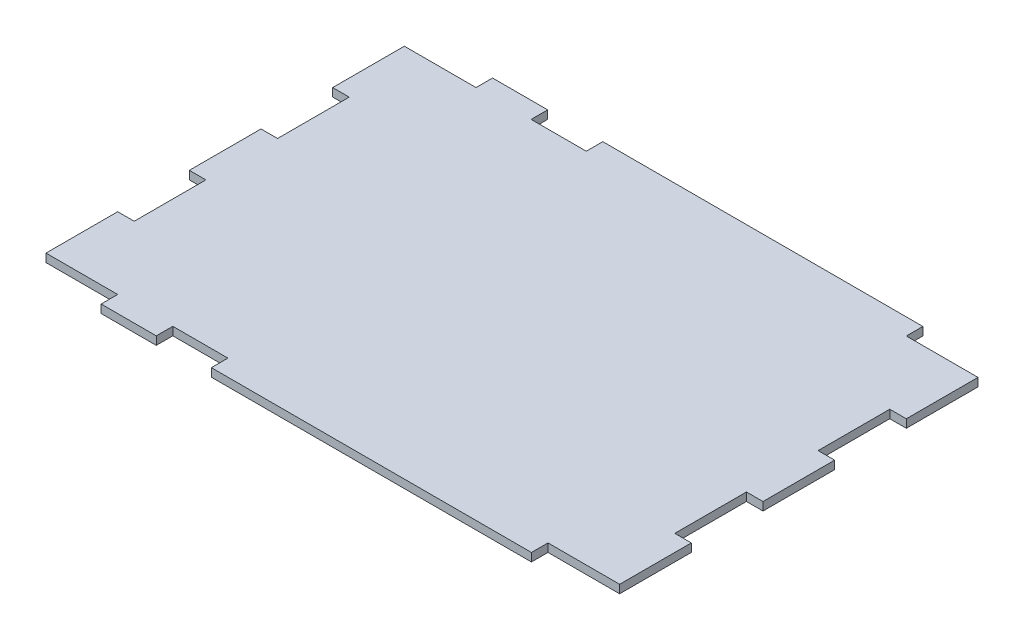
SolidWorks part; units mm, degrees
ref_plane "Front Plane" through (0, 0, 0) normal (0, 0, 1) x (1, 0, 0)
ref_plane "Top Plane" through (0, 0, 0) normal (0, 1, 0) x (1, 0, 0)
ref_plane "Right Plane" through (0, 0, 0) normal (1, 0, 0) x (0, 0, -1)
sketch "Sketch2" plane through (0, 0, 0) normal (0, 1, 0) x (1, 0, 0)
  line L0 (-122.9114, -52) -> (-128.9114, -52)
  line L1 (-122.9114, 78) -> (-102.9114, 78)
  line L3 (-122.9114, -52) -> (-102.9114, -52)
  line L4 (73.1886, 52) -> (73.1886, 26)
  line L5 (-128.9114, -52) -> (-128.9114, -26)
  line L6 (-128.9114, -26) -> (-122.9114, -26)
  line L7 (-122.9114, 0) -> (-128.9114, 0)
  line L8 (-128.9114, 0) -> (-128.9114, 26)
  line L9 (-128.9114, 26) -> (-122.9114, 26)
  line L10 (-122.9114, 52) -> (-122.9114, 26)
  line L11 (-122.9114, 52) -> (-128.9114, 52)
  line L12 (-128.9114, 52) -> (-128.9114, 78)
  line L13 (-128.9114, 78) -> (-122.9114, 78)
  line L14 (-122.9114, 0) -> (-122.9114, -26)
  line L15 (-122.9114, 78) -> (-122.9114, -52) construction
  line L16 (53.1886, 78) -> (79.1886, 78)
  line L18 (79.1886, 52) -> (79.1886, 78)
  line L19 (73.1886, 52) -> (79.1886, 52)
  line L20 (79.1886, 26) -> (73.1886, 26)
  line L21 (79.1886, 0) -> (79.1886, 26)
  line L22 (73.1886, 0) -> (79.1886, 0)
  line L23 (79.1886, -26) -> (73.1886, -26)
  line L24 (79.1886, -52) -> (79.1886, -26)
  line L25 (73.1886, -52) -> (79.1886, -52)
  line L26 (73.1886, 0) -> (73.1886, -26)
  line L27 (-102.9114, 78) -> (-102.9114, 84)
  line L28 (-102.9114, 84) -> (-82.9114, 84)
  line L29 (-82.9114, 84) -> (-82.9114, 78)
  line L30 (-82.9114, 78) -> (-62.9114, 78)
  line L31 (-128.9114, 13) -> (-122.9114, 13) construction
  line L32 (-82.9114, -58) -> (-82.9114, -52)
  line L33 (-102.9114, -58) -> (-82.9114, -58)
  line L34 (-102.9114, -52) -> (-102.9114, -58)
  line L35 (-82.9114, -52) -> (-62.9114, -52)
  line L36 (-62.9114, 78) -> (-62.9114, 84)
  line L37 (-62.9114, 84) -> (53.1886, 84)
  line L38 (53.1886, 84) -> (53.1886, 78)
  line L39 (-128.9114, 13) -> (79.1886, 13) construction
  line L40 (53.1886, -58) -> (53.1886, -52)
  line L41 (-62.9114, -58) -> (53.1886, -58)
  line L42 (-62.9114, -52) -> (-62.9114, -58)
  line L43 (53.1886, -52) -> (73.1886, -52)
  line L44 (-62.9114, 84) -> (-46.5781, 84) construction
  line L45 (-46.5781, 84) -> (-28.1281, 84) construction
  line L46 (-28.1281, 84) -> (39.4586, 84) construction
  line L47 (39.4586, 84) -> (21.0086, 84) construction
  line L48 (-46.5781, 84) -> (-46.5781, -58) construction
  line L49 (-28.1281, 84) -> (-28.1281, -58) construction
  line L50 (21.0086, 84) -> (21.0086, -58) construction
  line L51 (39.4586, 84) -> (39.4586, -58) construction
  dimension "D1" = 196.1
  dimension "D2" = 6
  dimension "D3" = 26
  dimension "D4" = 26
  dimension "D5" = 26
  dimension "D6" = 26
  dimension "D7" = 20
  dimension "D8" = 6
  dimension "D9" = 6
  dimension "D10" = 6
  dimension "D11" = 6
  dimension "D12" = 6
  dimension "D13" = 26
  dimension "D14" = 26
  dimension "D15" = 6
  dimension "D16" = 6
  dimension "D17" = 6
  dimension "D18" = 6
  dimension "D19" = 20
  dimension "D20" = 6
  dimension "D21" = 6
  dimension "D22" = 26
  dimension "D23" = 26
  dimension "D24" = 26
  dimension "D25" = 26
  dimension "D26" = 16.3333
  dimension "D27" = 18.45
  dimension "D28" = 13.73
  dimension "D29" = 18.45
  dimension "D30" = 116.1
extrude "Boss-Extrude1" add sketch "Sketch2" along normal blind 3
sketch "Sketch4" plane through (0, 3, 0) normal (0, 1, 0) x (1, 0, 0)
  line L0 (-48.3469, 71.7805) -> (-48.3469, 56.7805)
  line L1 (-45.8469, 81.7805) -> (-45.8469, 66.7805)
  line L2 (-43.3469, 71.7805) -> (-43.3469, 56.7805)
  line L3 (-40.8469, 81.7805) -> (-40.8469, 66.7805)
  line L4 (-38.3469, 71.7805) -> (-38.3469, 56.7805)
  line L5 (-35.8469, 81.7805) -> (-35.8469, 66.7805)
  line L6 (-33.3469, 71.7805) -> (-33.3469, 56.7805)
  line L7 (-30.8469, 81.7805) -> (-30.8469, 66.7805)
  line L8 (-28.3469, 71.7805) -> (-28.3469, 56.7805)
  line L9 (-25.8469, 81.7805) -> (-25.8469, 66.7805)
  line L10 (-23.3469, 71.7805) -> (-23.3469, 56.7805)
  line L12 (-48.3469, 51.7805) -> (-48.3469, 36.7805)
  line L13 (-45.8469, 61.7805) -> (-45.8469, 46.7805)
  line L14 (-43.3469, 51.7805) -> (-43.3469, 36.7805)
  line L15 (-40.8469, 61.7805) -> (-40.8469, 46.7805)
  line L16 (-38.3469, 51.7805) -> (-38.3469, 36.7805)
  line L17 (-35.8469, 61.7805) -> (-35.8469, 46.7805)
  line L18 (-33.3469, 51.7805) -> (-33.3469, 36.7805)
  line L19 (-30.8469, 61.7805) -> (-30.8469, 46.7805)
  line L20 (-28.3469, 51.7805) -> (-28.3469, 36.7805)
  line L21 (-25.8469, 61.7805) -> (-25.8469, 46.7805)
  line L22 (-23.3469, 51.7805) -> (-23.3469, 36.7805)
  line L24 (-48.3469, 31.7805) -> (-48.3469, 16.7805)
  line L25 (-45.8469, 41.7805) -> (-45.8469, 26.7805)
  line L26 (-43.3469, 31.7805) -> (-43.3469, 16.7805)
  line L27 (-40.8469, 41.7805) -> (-40.8469, 26.7805)
  line L28 (-38.3469, 31.7805) -> (-38.3469, 16.7805)
  line L29 (-35.8469, 41.7805) -> (-35.8469, 26.7805)
  line L30 (-33.3469, 31.7805) -> (-33.3469, 16.7805)
  line L31 (-30.8469, 41.7805) -> (-30.8469, 26.7805)
  line L32 (-28.3469, 31.7805) -> (-28.3469, 16.7805)
  line L33 (-25.8469, 41.7805) -> (-25.8469, 26.7805)
  line L34 (-23.3469, 31.7805) -> (-23.3469, 16.7805)
  line L36 (-48.3469, 11.7805) -> (-48.3469, -3.2195)
  line L37 (-45.8469, 21.7805) -> (-45.8469, 6.7805)
  line L38 (-43.3469, 11.7805) -> (-43.3469, -3.2195)
  line L39 (-40.8469, 21.7805) -> (-40.8469, 6.7805)
  line L40 (-38.3469, 11.7805) -> (-38.3469, -3.2195)
  line L41 (-35.8469, 21.7805) -> (-35.8469, 6.7805)
  line L42 (-33.3469, 11.7805) -> (-33.3469, -3.2195)
  line L43 (-30.8469, 21.7805) -> (-30.8469, 6.7805)
  line L44 (-28.3469, 11.7805) -> (-28.3469, -3.2195)
  line L45 (-25.8469, 21.7805) -> (-25.8469, 6.7805)
  line L46 (-23.3469, 11.7805) -> (-23.3469, -3.2195)
  line L48 (-48.3469, -8.2195) -> (-48.3469, -23.2195)
  line L49 (-45.8469, 1.7805) -> (-45.8469, -13.2195)
  line L50 (-43.3469, -8.2195) -> (-43.3469, -23.2195)
  line L51 (-40.8469, 1.7805) -> (-40.8469, -13.2195)
  line L52 (-38.3469, -8.2195) -> (-38.3469, -23.2195)
  line L53 (-35.8469, 1.7805) -> (-35.8469, -13.2195)
  line L54 (-33.3469, -8.2195) -> (-33.3469, -23.2195)
  line L55 (-30.8469, 1.7805) -> (-30.8469, -13.2195)
  line L56 (-28.3469, -8.2195) -> (-28.3469, -23.2195)
  line L57 (-25.8469, 1.7805) -> (-25.8469, -13.2195)
  line L58 (-23.3469, -8.2195) -> (-23.3469, -23.2195)
  line L60 (-48.3469, -28.2195) -> (-48.3469, -43.2195)
  line L61 (-45.8469, -18.2195) -> (-45.8469, -33.2195)
  line L62 (-43.3469, -28.2195) -> (-43.3469, -43.2195)
  line L63 (-40.8469, -18.2195) -> (-40.8469, -33.2195)
  line L64 (-38.3469, -28.2195) -> (-38.3469, -43.2195)
  line L65 (-35.8469, -18.2195) -> (-35.8469, -33.2195)
  line L66 (-33.3469, -28.2195) -> (-33.3469, -43.2195)
  line L67 (-30.8469, -18.2195) -> (-30.8469, -33.2195)
  line L68 (-28.3469, -28.2195) -> (-28.3469, -43.2195)
  line L69 (-25.8469, -18.2195) -> (-25.8469, -33.2195)
  line L70 (-23.3469, -28.2195) -> (-23.3469, -43.2195)
  line L72 (-48.1958, -48.6466) -> (-48.1958, -58)
  line L73 (-45.8469, -38.2195) -> (-45.8469, -53.2195)
  line L74 (-43.1958, -48.6466) -> (-43.1958, -58)
  line L75 (-40.8469, -38.2195) -> (-40.8469, -53.2195)
  line L76 (-38.3469, -48.6466) -> (-38.3469, -58)
  line L77 (-35.8469, -38.2195) -> (-35.8469, -53.2195)
  line L78 (-33.3739, -48.6466) -> (-33.3739, -58)
  line L79 (-30.8469, -38.2195) -> (-30.8469, -53.2195)
  line L80 (-28.1905, -48.6466) -> (-28.1905, -58)
  line L81 (-25.8469, -38.2195) -> (-25.8469, -53.2195)
  line L82 (-23.3469, -48.6466) -> (-23.3469, -58)
  line L84 (-48.3469, 84) -> (-48.3469, 75.3572)
  line L85 (-43.3469, 84) -> (-43.3469, 75.3572)
  line L86 (-38.3403, 84) -> (-38.3469, 75.3572)
  line L87 (-33.3738, 84) -> (-33.3469, 75.3572)
  line L88 (-28.3738, 84) -> (-28.3469, 75.3572)
  line L89 (-23.3738, 84) -> (-23.3469, 75.3572)
  line L90 (53.1886, 84) -> (-62.9114, 84) construction
  line L91 (-62.9114, -58) -> (53.1886, -58) construction
  line L92 (15.5348, 71.2734) -> (15.5348, 56.2734)
  line L93 (18.0348, 81.2734) -> (18.0348, 66.2734)
  line L94 (20.5348, 71.2734) -> (20.5348, 56.2734)
  line L95 (23.0348, 81.2734) -> (23.0348, 66.2734)
  line L96 (25.5348, 71.2734) -> (25.5348, 56.2734)
  line L97 (28.0348, 81.2734) -> (28.0348, 66.2734)
  line L98 (30.5348, 71.2734) -> (30.5348, 56.2734)
  line L99 (33.0348, 81.2734) -> (33.0348, 66.2734)
  line L100 (35.5348, 71.2734) -> (35.5348, 56.2734)
  line L101 (38.0348, 81.2734) -> (38.0348, 66.2734)
  line L102 (40.5348, 71.2734) -> (40.5348, 56.2734)
  line L104 (15.5348, 51.2734) -> (15.5348, 36.2734)
  line L105 (18.0348, 61.2734) -> (18.0348, 46.2734)
  line L106 (20.5348, 51.2734) -> (20.5348, 36.2734)
  line L107 (23.0348, 61.2734) -> (23.0348, 46.2734)
  line L108 (25.5348, 51.2734) -> (25.5348, 36.2734)
  line L109 (28.0348, 61.2734) -> (28.0348, 46.2734)
  line L110 (30.5348, 51.2734) -> (30.5348, 36.2734)
  line L111 (33.0348, 61.2734) -> (33.0348, 46.2734)
  line L112 (35.5348, 51.2734) -> (35.5348, 36.2734)
  line L113 (38.0348, 61.2734) -> (38.0348, 46.2734)
  line L114 (40.5348, 51.2734) -> (40.5348, 36.2734)
  line L116 (15.5348, 31.2734) -> (15.5348, 16.2734)
  line L117 (18.0348, 41.2734) -> (18.0348, 26.2734)
  line L118 (20.5348, 31.2734) -> (20.5348, 16.2734)
  line L119 (23.0348, 41.2734) -> (23.0348, 26.2734)
  line L120 (25.5348, 31.2734) -> (25.5348, 16.2734)
  line L121 (28.0348, 41.2734) -> (28.0348, 26.2734)
  line L122 (30.5348, 31.2734) -> (30.5348, 16.2734)
  line L123 (33.0348, 41.2734) -> (33.0348, 26.2734)
  line L124 (35.5348, 31.2734) -> (35.5348, 16.2734)
  line L125 (38.0348, 41.2734) -> (38.0348, 26.2734)
  line L126 (40.5348, 31.2734) -> (40.5348, 16.2734)
  line L128 (15.5348, 11.2734) -> (15.5348, -3.7266)
  line L129 (18.0348, 21.2734) -> (18.0348, 6.2734)
  line L130 (20.5348, 11.2734) -> (20.5348, -3.7266)
  line L131 (23.0348, 21.2734) -> (23.0348, 6.2734)
  line L132 (25.5348, 11.2734) -> (25.5348, -3.7266)
  line L133 (28.0348, 21.2734) -> (28.0348, 6.2734)
  line L134 (30.5348, 11.2734) -> (30.5348, -3.7266)
  line L135 (33.0348, 21.2734) -> (33.0348, 6.2734)
  line L136 (35.5348, 11.2734) -> (35.5348, -3.7266)
  line L137 (38.0348, 21.2734) -> (38.0348, 6.2734)
  line L138 (40.5348, 11.2734) -> (40.5348, -3.7266)
  line L140 (15.5348, -8.7266) -> (15.5348, -23.7266)
  line L141 (18.0348, 1.2734) -> (18.0348, -13.7266)
  line L142 (20.5348, -8.7266) -> (20.5348, -23.7266)
  line L143 (23.0348, 1.2734) -> (23.0348, -13.7266)
  line L144 (25.5348, -8.7266) -> (25.5348, -23.7266)
  line L145 (28.0348, 1.2734) -> (28.0348, -13.7266)
  line L146 (30.5348, -8.7266) -> (30.5348, -23.7266)
  line L147 (33.0348, 1.2734) -> (33.0348, -13.7266)
  line L148 (35.5348, -8.7266) -> (35.5348, -23.7266)
  line L149 (38.0348, 1.2734) -> (38.0348, -13.7266)
  line L150 (40.5348, -8.7266) -> (40.5348, -23.7266)
  line L152 (15.5348, -28.7266) -> (15.5348, -43.7266)
  line L153 (18.0348, -18.7266) -> (18.0348, -33.7266)
  line L154 (20.5348, -28.7266) -> (20.5348, -43.7266)
  line L155 (23.0348, -18.7266) -> (23.0348, -33.7266)
  line L156 (25.5348, -28.7266) -> (25.5348, -43.7266)
  line L157 (28.0348, -18.7266) -> (28.0348, -33.7266)
  line L158 (30.5348, -28.7266) -> (30.5348, -43.7266)
  line L159 (33.0348, -18.7266) -> (33.0348, -33.7266)
  line L160 (35.5348, -28.7266) -> (35.5348, -43.7266)
  line L161 (38.0348, -18.7266) -> (38.0348, -33.7266)
  line L162 (40.5348, -28.7266) -> (40.5348, -43.7266)
  line L164 (15.6859, -48.8459) -> (15.6859, -58)
  line L165 (18.0348, -38.7266) -> (18.0348, -53.7266)
  line L166 (20.6859, -48.8459) -> (20.6859, -58)
  line L167 (23.0348, -38.7266) -> (23.0348, -53.7266)
  line L168 (25.5348, -48.8459) -> (25.5348, -58)
  line L169 (28.0348, -38.7266) -> (28.0348, -53.7266)
  line L170 (30.5079, -48.8459) -> (30.5079, -58)
  line L171 (33.0348, -38.7266) -> (33.0348, -53.7266)
  line L172 (35.6913, -48.8459) -> (35.6913, -58)
  line L173 (38.0348, -38.7266) -> (38.0348, -53.7266)
  line L174 (40.5348, -48.8459) -> (40.5348, -58)
  line L176 (15.5348, 84) -> (15.5348, 75.1578)
  line L177 (20.5348, 84) -> (20.5348, 75.1578)
  line L178 (25.5416, 84) -> (25.5348, 75.1578)
  line L179 (30.5073, 84) -> (30.5348, 75.1578)
  line L180 (35.5073, 84) -> (35.5348, 75.1578)
  line L181 (40.5073, 84) -> (40.5348, 75.1578)
